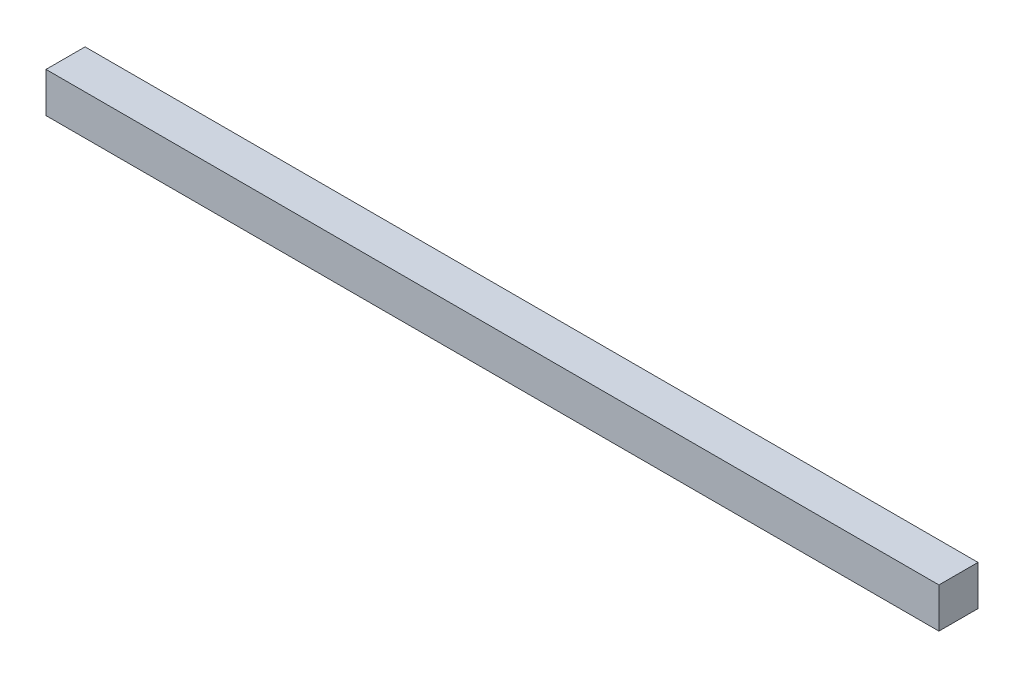
SolidWorks part; units mm, degrees
ref_plane "Спереди" through (0, 0, 0) normal (0, 0, 1) x (1, 0, 0)
ref_plane "Сверху" through (0, 0, 0) normal (0, 1, 0) x (1, 0, 0)
ref_plane "Справа" through (0, 0, 0) normal (1, 0, 0) x (0, 0, -1)
other "Configuration Table"
sketch "Ширина_фанера_плюс_зазор" plane through (0, 0, 0) normal (0, 0, 1) x (1, 0, 0)
  line L0 (-0.1, -3.075) -> (137.075, -3.075)
  line L1 (137.075, -3.075) -> (137.075, 3.075)
  line L2 (137.075, 3.075) -> (-0.1, 3.075)
  line L3 (-0.1, 3.075) -> (-0.1, -3.075)
  line L4 (-0.1, -3.075) -> (137.075, 3.075) construction
  point P4 (68.4875, 0)
  dimension "Ширина" = 137.175
  dimension "Глубина" = 6.15
  dimension "Положение_ПоОси" = 68.4875
extrude "Прямой_участок" add sketch "Ширина_фанера_плюс_зазор" along normal blind 6
equation "\"D1@Прямой_участок\" = \"Толщина тонких панелей\""
equation "\"Глубина@Ширина_фанера_плюс_зазор\"  = \"Толщина горизонтальных плит\"+\"Посадочный зазор\""
equation "\"Фанера\"= \"Толщина горизонтальных плит\""
equation "\"Ширина шипа\"=16"
equation "\"Межосевое шипов\"=40"
equation "\"Посадочный зазор\"=0.15"
equation "\"Основная фреза\"=6"
equation "\"Мелкая фреза\"=6"
equation "\"Запас разгрузки\"=0.05"
equation "\"Ширина образца\"=84"
equation "\"Высота образца\"=50"
equation "\"Канал М6\"=6"
equation "\"Гайка под ключ\"=10.3"
equation "\"Длина кармана гайки\"=6.2"
equation "\"Отступ гайки\"=12"
equation "\"Ширина@Ширина_фанера_плюс_зазор\" = (\"Глубина ячейки\"+3*\"Толщина тонких панелей\")/2+(\"Толщина вертикальных стенок\"+\"Посадочный зазор\")/2+0.1"
equation "\"Положение_ПоОси@Ширина_фанера_плюс_зазор\" = (\"Глубина ячейки\"+3*\"Толщина тонких панелей\")/4+(\"Толщина вертикальных стенок\"+\"Посадочный зазор\")/4-0.05"
equation "\"Ширина груза\"= 160"
equation "\"Глубина груза\"= 240"
equation "\"Высота груза\"= 160"
equation "\"Ширина ячейки\"= \"Ширина груза\" + 10"
equation "\"Глубина ячейки\"= \"Глубина груза\" + 10"
equation "\"Высота ячейки\"= \"Высота груза\" + 10 + 13"
equation "\"Колво ячеек ширина\"= 2"
equation "\"Колво ячеек высота\"= 2"
equation "\"Толщина стенки\" = \"Толщина тонких панелей\""
equation "\"Крепление дверцы\"= 5 "
equation "\"Ширина рейки\"= \"Толщина шестерни\""
equation "\"Высота рейки\"= 20"
equation "\"Высота пола\" = 2*\"Толщина тонких панелей\""
equation "\"Колво полозьев\"= 5"
equation "\"Отступ рейки\"= 20"
equation "\"Глубина каретки\"= \"Глубина ячейки\" + 30 + \"Мотор Y высота корпуса\" + 20"
equation "\"Длинна рейки\" = (\"Ширина ячейки\"+\"Толщина вертикальных стенок\"+\"Крепление дверцы\")*\"Колво ячеек ширина\"+\"Ширина ячейки выгрузки\"*\"Колво выгрузки\"+\"Толщина вертикальных стенок\"+2*\"Отступ крепления мотора фиксации\"-\"Крепление дверцы\"*\"Колво ячеек ширина\""
equation "\"Отступ шпильки\"= 26"
equation "\"Диаметр шпильки\"= 5"
equation "\"Длинна шпильки\" = (\"Высота ячейки\"+\"Толщина горизонтальных плит\"+\"Высота пола\")*\"Колво ячеек высота\"+2*(\"Толщина горизонтальных плит\"+\"Отступ рейки\")"
equation "\"Ширина пластины\"= 50  "
equation "\"Высота зона выгрузки\"= \"Высота ячейки\" * 2 + \"Толщина стенки\" * 2"
equation "\"Колво выгрузки\"= 1"
equation "\"Ширина ячейки выгрузки\" = \"Ширина ячейки\"+\"Толщина вертикальных стенок\"+2*\"Отступ крепления мотора фиксации\""
equation "\"Отступ крепления мотора фиксации\" = (\"Ширина пластины\"+20-\"Толщина вертикальных стенок\")/2"
equation "\"Мотор X ширина корпуса\"= 42.3"
equation "\"Мотор X высота корпуса\"= 42.3"
equation "\"Мотор X длина корпуса\"= 40"
equation "\"Мотор X вылет вала\"= 19.8"
equation "\"Мотор Y ширина корпуса\"= 42.3"
equation "\"Мотор Y высота корпуса\"= 42.3"
equation "\"Мотор Y длина корпуса\"= 48"
equation "\"Мотор Y вылет вала\"= 30"
equation "\"Мотор Z ширина корпуса\"= 42"
equation "\"Мотор Z высота корпуса\"= 42"
equation "\"Мотор Z длина корпуса\"= 40"
equation "\"Мотор Z вылет вала\"= 23"
equation "\"Мотор диаметр вала ПРЕДВ\"= 5"
equation "\"Мотор шаг крепления ПРЕДВ\"= 31"
equation "\"Мотор диаметр отверстий ПРЕДВ\"= 3"
equation "\"Мотор глубина отверстий ПРЕДВ\"= 4.5"
equation "\"Мотор диаметр буртика ПРЕДВ\"= 22"
equation "\"Мотор высота буртика ПРЕДВ\"= 2"
equation "\"Мотор диаметр шкива ПРЕДВ\"= 16"
equation "\"Мотор длина шкива ПРЕДВ\"= 12"
equation "\"Мотор отступ шкива ПРЕДВ\"= 5"
equation "\"Мотор X шаг градусов\"= 1.8"
equation "\"Мотор Y шаг градусов\"= 1.8"
equation "\"Мотор Z шаг градусов\"= 1.8"
equation "\"Мотор Y диаметр ротора\"= 25.78"
equation "\"Толщина шестерни\"= 10"
equation "\"Толщина тонких панелей\" = 6"
equation "\"Толщина вертикальных стенок\" = 6"
equation "\"Толщина горизонтальных плит\" = 6"
equation "\"Базовая высота корпуса\"= (\"Высота ячейки\"+\"Толщина тонких панелей\"+\"Высота пола\")*\"Колво ячеек высота\"+6*\"Толщина тонких панелей\"+\"Мотор X ширина корпуса\"+\"Мотор Y ширина корпуса\"+75"
equation "\"Высота корпуса\"= (\"Высота ячейки\"+\"Толщина горизонтальных плит\"+\"Высота пола\")*\"Колво ячеек высота\"+2*\"Толщина горизонтальных плит\"+4*\"Толщина тонких панелей\"+\"Мотор X ширина корпуса\"+\"Мотор Y ширина корпуса\"+75"
equation "\"Смещение центра корпуса\"= (\"Высота корпуса\"-\"Базовая высота корпуса\")/2-(\"Толщина горизонтальных плит\"-\"Толщина тонких панелей\")"
equation "\"Отметка пола\"= -\"Базовая высота корпуса\"/2+\"Толщина тонких панелей\""
equation "\"Отметка потолка\"= \"Отметка пола\"+\"Высота корпуса\"-2*\"Толщина горизонтальных плит\""
equation "\"Отметка верхней полки\"= \"Отметка потолка\"-(28+\"Толщина тонких панелей\")-\"Высота ячейки\"-\"Высота пола\""
equation "\"Отметка нижней полки\"= \"Отметка верхней полки\"-\"Высота ячейки\"-\"Высота пола\"-\"Толщина горизонтальных плит\""
